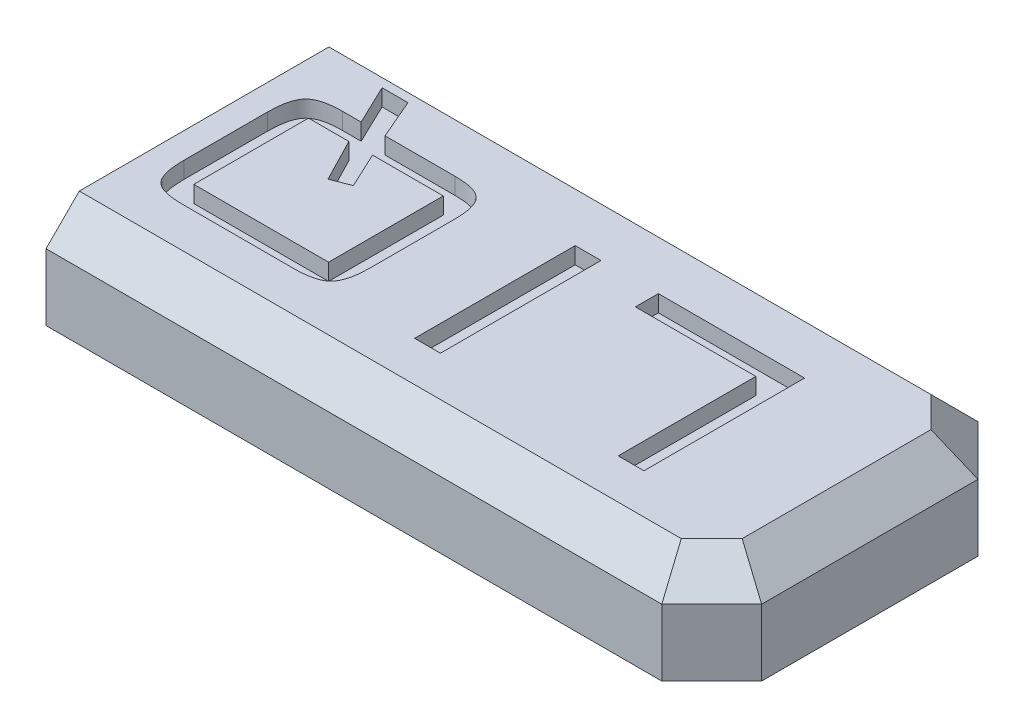
SolidWorks part; units mm, degrees
ref_plane "Front Plane" through (0, 0, 0) normal (0, 0, 1) x (1, 0, 0)
ref_plane "Top Plane" through (0, 0, 0) normal (0, 1, 0) x (1, 0, 0)
ref_plane "Right Plane" through (0, 0, 0) normal (1, 0, 0) x (0, 0, -1)
sketch "Sketch1" plane through (0, -196.7989, 0) normal (0, 1, 0) x (1, 0, 0)
  line L0 (-111.7262, -390.6201) -> (-307.2262, -390.6201) construction
  line L1 (-110.6955, -390.6201) -> (-70.6955, -390.6201)
  line L3 (-110.6955, -409.6201) -> (-70.6955, -409.6201)
  line L4 (-70.6955, -390.6201) -> (-70.6955, -409.6201)
  line L5 (-110.6955, -409.6201) -> (-151.6955, -409.6201)
  line L7 (-110.6955, -390.6201) -> (-151.6955, -390.6201)
  line L8 (-151.6955, -409.6201) -> (-151.6955, -390.6201)
  dimension "D1" = 40
  dimension "D2" = 19
  dimension "D3" = 41
extrude "Boss-Extrude1" add sketch "Sketch1" along normal blind 6
sketch "Sketch2" plane through (0, -190.7989, 0) normal (0, 1, 0) x (1, 0, 0)
  line L0 (-148.0955, -395.5609) -> (-72.8625, -395.5609) construction
  line L3 (-70.6955, -390.6201) -> (-151.6955, -390.6201) construction
  line L4 (-151.6955, -390.6201) -> (-151.6955, -409.6201) construction
  text T0 "LIQUID" font "BankGothic Lt BT" height in points 36
  dimension "D1" = 360
  dimension "D2" = 3.6
extrude "Cut-Extrude1" cut sketch "Sketch2" against normal blind 1
ref_plane "Plane1" through (-70.6955, -190.7989, 409.6201) normal (1, 0, 0) x (0, 0, -1)
sketch "Sketch4" plane through (0, -190.7989, 0) normal (0, 1, 0) x (1, 0, 0)
  line L0 (-111.1955, -390.6201) -> (-111.1955, -409.6201) construction
  line L1 (-70.6955, -390.6201) -> (-151.6955, -390.6201) construction
  line L2 (-151.6955, -409.6201) -> (-70.6955, -409.6201) construction
  line L4 (-111.1955, -409.6201) -> (-154.5434, -409.6201)
  line L5 (-111.1955, -409.6201) -> (-111.1955, -383.2905)
  line L6 (-111.1955, -383.2905) -> (-154.5434, -383.2905)
  line L7 (-154.5434, -409.6201) -> (-154.5434, -383.2905)
extrude "Cut-Extrude2" cut sketch "Sketch4" against normal blind 10
chamfer "Chamfer1" distance 3 angle 45 2 edges at (-70.6955, -193.7989, 390.6201) (-70.6955, -193.7989, 409.6201)
chamfer "Chamfer2" distance 2 angle 45 5 edges at (-92.4455, -190.7989, 390.6201) (-72.1955, -190.7989, 392.1201) (-70.6955, -190.7989, 400.1201) (-72.1955, -190.7989, 408.1201) (-92.4455, -190.7989, 409.6201)
sketch "Sketch5" plane through (-111.1955, 0, 0) normal (-1, 0, 0) x (0, 0, 1)
  line L1 (384.0476, -184.6777) -> (418.9077, -184.6777)
  line L2 (384.0476, -184.6777) -> (384.0476, -202.5438)
  line L3 (384.0476, -202.5438) -> (418.9077, -202.5438)
  line L4 (418.9077, -184.6777) -> (418.9077, -202.5438)
extrude "Cut-Extrude3" cut sketch "Sketch5" against normal blind 0.5
sketch "Sketch6" plane through (0, -196.7989, 0) normal (0, -1, 0) x (1, 0, 0)
  line L0 (-110.6955, 409.6201) -> (-110.6955, 390.6201) construction
  line L1 (-110.6955, 409.6201) -> (-73.6955, 409.6201) construction
  circle A0 centre (-91.1955, 400.1201) radius 4.1
  dimension "D1" = 8.2
  dimension "D2" = 19.5
  dimension "D3" = 9.5
extrude "Cut-Extrude4" cut sketch "Sketch6" against normal blind 3.4
